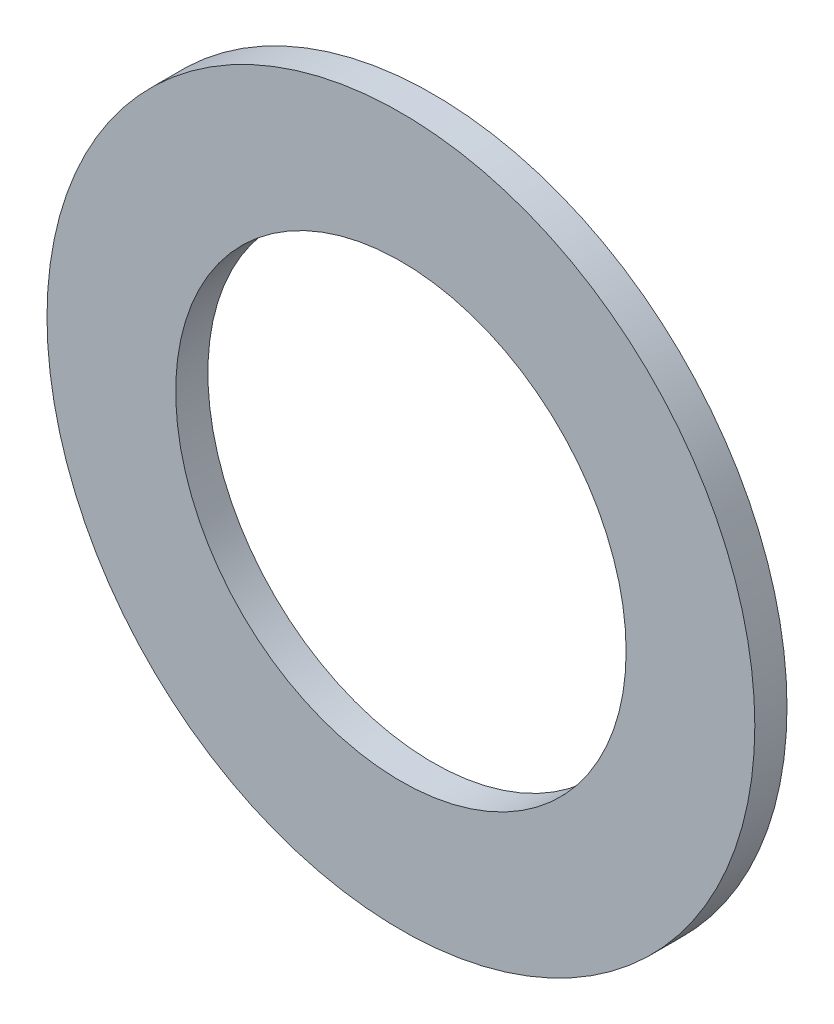
SolidWorks part; units mm, degrees
material "Acier allié inoxydable"
ref_plane "Plan de face" through (0, 0, 0) normal (0, 0, 1) x (1, 0, 0)
ref_plane "Plan de dessus" through (0, 0, 0) normal (0, 1, 0) x (1, 0, 0)
ref_plane "Plan de droite" through (0, 0, 0) normal (1, 0, 0) x (0, 0, -1)
sketch "Esquisse1" plane through (0, 0, 0) normal (0, 0, 1) x (1, 0, 0)
  circle A0 centre (0, 0) radius 5.5
  circle A1 centre (0, 0) radius 3.5
  dimension "D1" = 11
  dimension "D2" = 7
extrude "Boss.-Extru.1" add sketch "Esquisse1" along normal blind 0.5
